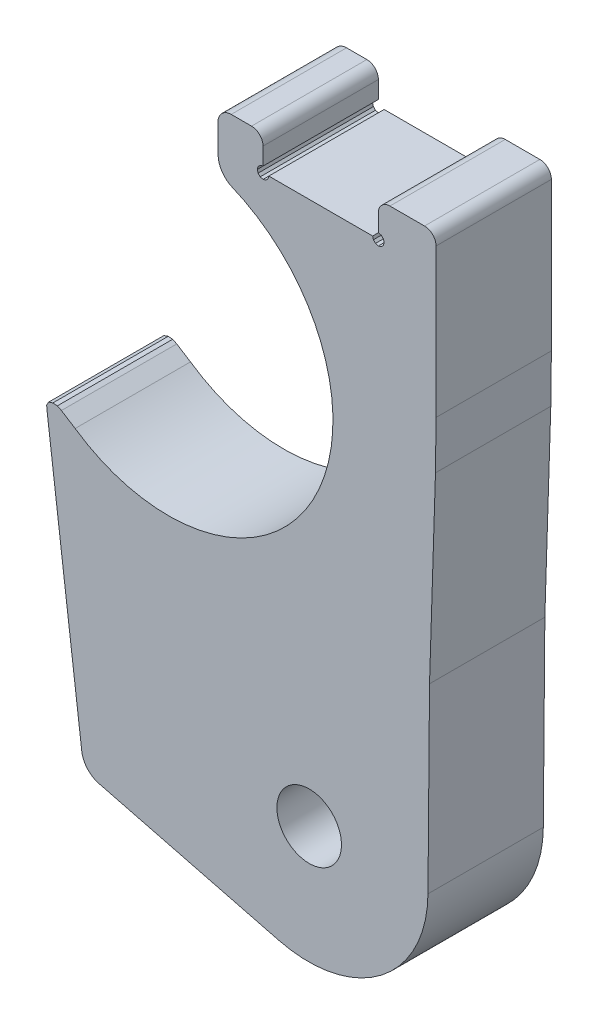
SolidWorks part; units mm, degrees
ref_plane "Plan de face" through (0, 0, 0) normal (0, 0, 1) x (1, 0, 0)
ref_plane "Plan de dessus" through (0, 0, 0) normal (0, 1, 0) x (1, 0, 0)
ref_plane "Plan de droite" through (0, 0, 0) normal (1, 0, 0) x (0, 0, -1)
ref_plane "Plan1" through (0, 0, 0) normal (0, 0, -1) x (-1, 0, 0)
sketch "Esquisse1" plane through (0, 0, 0) normal (0, 0, -1) x (-1, 0, 0)
  line L2 (-15.1858, 0.1703) -> (-7.3862, 2.1578)
  line L6 (-6.6409, 3.0026) -> (-5.1454, 14.9533)
  line L7 (-5.1454, 14.9533) -> (-5.1167, 15.2349)
  line L8 (-5.1167, 15.2349) -> (-5.2017, 15.388)
  line L9 (-5.2017, 15.388) -> (-5.3869, 15.451)
  line L10 (-5.3869, 15.451) -> (-5.5821, 15.4383)
  line L11 (-5.5821, 15.4383) -> (-5.7574, 15.3516)
  line L12 (-5.7574, 15.3516) -> (-6.3532, 14.9744)
  line L34 (-12.5529, 28.3574) -> (-12.5529, 29.6663)
  line L38 (-13.119, 30.15) -> (-14, 30.15)
  line L42 (-14.5, 29.65) -> (-14.5, 28.9)
  line L43 (-14.5, 28.9) -> (-14.375, 28.8665)
  line L44 (-14.375, 28.8665) -> (-14.2835, 28.775)
  line L45 (-14.2835, 28.775) -> (-14.25, 28.65)
  line L46 (-14.25, 28.65) -> (-14.2835, 28.525)
  line L47 (-14.2835, 28.525) -> (-14.375, 28.4335)
  line L48 (-14.375, 28.4335) -> (-14.5, 28.4)
  line L49 (-14.5, 28.4) -> (-14.625, 28.4335)
  line L50 (-14.625, 28.4335) -> (-14.7165, 28.525)
  line L51 (-14.7165, 28.525) -> (-14.75, 28.65)
  line L52 (-14.75, 28.65) -> (-19.25, 28.65)
  line L53 (-19.25, 28.65) -> (-19.2835, 28.525)
  line L54 (-19.2835, 28.525) -> (-19.375, 28.4335)
  line L55 (-19.375, 28.4335) -> (-19.5, 28.4)
  line L56 (-19.5, 28.4) -> (-19.625, 28.4335)
  line L57 (-19.625, 28.4335) -> (-19.7165, 28.525)
  line L58 (-19.7165, 28.525) -> (-19.75, 28.65)
  line L59 (-19.75, 28.65) -> (-19.7165, 28.775)
  line L60 (-19.7165, 28.775) -> (-19.625, 28.8665)
  line L61 (-19.625, 28.8665) -> (-19.5, 28.9)
  line L62 (-19.5, 28.9) -> (-19.5, 29.65)
  line L66 (-20, 30.15) -> (-21.5, 30.15)
  line L70 (-22, 29.65) -> (-22, 23.2122)
  line L71 (-22, 23.2122) -> (-21.9745, 21.1187)
  line L72 (-21.9745, 21.1187) -> (-21.7169, 13.0698)
  line L73 (-21.7169, 13.0698) -> (-21.65, 5.1502)
  circle A0 centre (-16.5004, 5.1149) radius 1.4
  arc A1 (-13.1272, 27.4526) -> (-6.3532, 14.9744) centre (-10.3925, 20.8594) ccw
  arc A2 (-19.5, 29.65) -> (-20, 30.15) centre (-20, 29.65) ccw
  arc A3 (-21.5, 30.15) -> (-22, 29.65) centre (-21.5, 29.65) ccw
  arc A4 (-21.65, 5.1502) -> (-15.1858, 0.1703) centre (-16.466, 5.194) ccw
  arc A5 (-7.3862, 2.1578) -> (-6.6409, 3.0026) centre (-7.6332, 3.1268) ccw
  arc A6 (-12.5529, 28.3574) -> (-13.1272, 27.4526) centre (-13.5529, 28.3574) cw
  arc A7 (-14.5, 29.65) -> (-14, 30.15) centre (-14, 29.65) cw
  arc A8 (-13.119, 30.15) -> (-12.5529, 29.6663) centre (-13.119, 29.5769) cw
  dimension "D1" = 2.8
  dimension "D2" = 14.2757
extrude "Boss.-Extru.1" add sketch "Esquisse1" against normal blind 5
